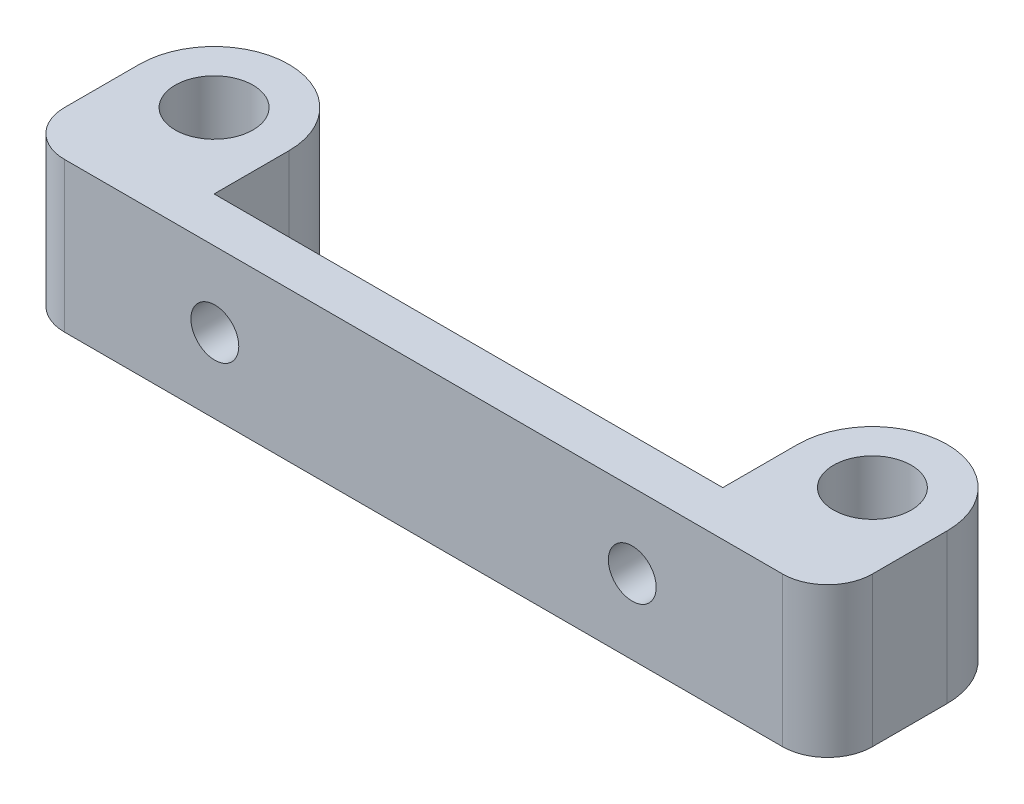
SolidWorks part; units mm, degrees
material "ABS"
ref_plane "前视基准面" through (0, 0, 0) normal (0, 0, 1) x (1, 0, 0)
ref_plane "上视基准面" through (0, 0, 0) normal (0, 1, 0) x (1, 0, 0)
ref_plane "右视基准面" through (0, 0, 0) normal (1, 0, 0) x (0, 0, -1)
sketch "草图1" plane through (0, 0, 0) normal (0, 0, 1) x (1, 0, 0)
  line L0 (-27, 0) -> (27, 0)
  line L1 (27, 0) -> (17, 0)
  line L2 (0, 0) -> (0, 5.4578) construction
  line L3 (-27, 0) -> (-17, 0)
  line L4 (-13.95, 0) -> (-13.95, 5)
  line L5 (-27, -5) -> (-27, 5)
  line L6 (-27, 5) -> (27, 5)
  line L7 (27, 5) -> (27, -5)
  line L8 (-27, -5) -> (27, -5)
  circle A1 centre (13.95, 0) radius 1.6
  circle A2 centre (-13.95, 0) radius 1.6
  point P14 (-27, 0)
  point P15 (-27, 0)
  dimension "D3" = 3.2
  dimension "D1" = 27
  dimension "D2" = 10
  dimension "D4" = 27.9
  dimension "D5" = 5
  dimension "D6" = 5
extrude "凸台-拉伸1" add sketch "草图1" along normal blind 3 contours L0 L2 L6 L4 A2 | L0 A2 L4 L6 L5 | L0 A2 L5 L8 L7 A1 | L2 L0 A1 L7 L6
sketch "草图2" plane through (0, 5, 0) normal (0, 1, 0) x (1, 0, 0)
  line L0 (-27, 0) -> (-22, 0) construction
  line L1 (-27, 0) -> (27, 0) construction
  line L2 (-22, 0) -> (-22, 5) construction
  line L3 (-27, 5) -> (-27, 0)
  line L4 (-17, 5) -> (-17, 0)
  line L5 (-17, 0) -> (-27, 0)
  line L6 (0, 0) -> (0, 9.1702) construction
  line L7 (22, 0) -> (22, 5) construction
  line L8 (27, 0) -> (22, 0) construction
  line L9 (17, 0) -> (27, 0)
  line L10 (17, 5) -> (17, 0)
  line L11 (27, 5) -> (27, 0)
  circle A0 centre (-22, 5) radius 5
  circle A1 centre (-22, 5) radius 2.6
  circle A2 centre (22, 5) radius 2.6
  circle A3 centre (22, 5) radius 5
  line M6 (27, 0) -> (-27, 0)
  dimension "D2" = 5.2
  dimension "D1" = 5
extrude "凸台-拉伸2" add sketch "草图2" against normal through all contours A0 A1 | A0 L4 M6 | A0 L3 L5 | L9 A3 L10 | A3 A2 | L11 A3 M6
fillet "圆角1" radius 3 2 edges at (-27, 0, 3) (27, 0, 3)
